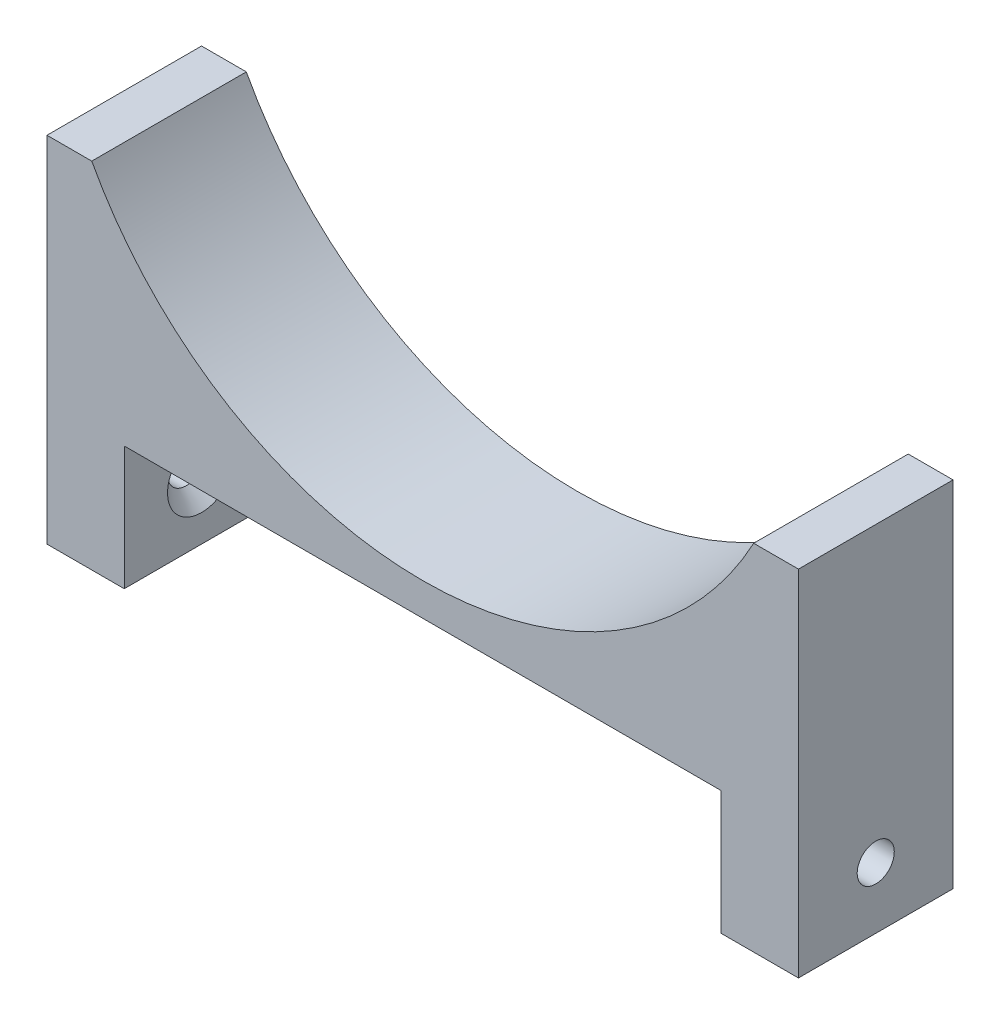
SolidWorks part; units mm, degrees
ref_plane "Płaszczyzna przednia" through (0, 0, 0) normal (0, 0, 1) x (1, 0, 0)
ref_plane "Płaszczyzna górna" through (0, 0, 0) normal (0, 1, 0) x (1, 0, 0)
ref_plane "Płaszczyzna prawa" through (0, 0, 0) normal (1, 0, 0) x (0, 0, -1)
sketch "Sketch1" plane through (0, 0, 0) normal (0, 0, 1) x (1, 0, 0)
  line L0 (-9.7094, -21.2696) -> (-4.7094, -21.2696)
  line L1 (-4.7094, -21.2696) -> (-4.7094, -13.2696)
  line L2 (-4.7094, -13.2696) -> (33.9106, -13.2696)
  line L3 (33.9106, -13.2696) -> (33.9106, -21.2696)
  line L4 (33.9106, -21.2696) -> (38.9106, -21.2696)
  line L5 (38.9106, -21.2696) -> (38.9106, 1.6414)
  line L6 (38.9106, 1.6414) -> (-9.7094, 1.6414)
  line L7 (-9.7094, 1.6414) -> (-9.7094, -21.2696)
  line L8 (14.6006, 13.1504) -> (14.6006, -40.5959) construction
  circle A0 centre (14.6006, 13.1504) radius 24.31
  dimension "D1" = 48.62
  dimension "48.62" = 48.62
  dimension "D2" = 34.42
  dimension "D3" = 5
  dimension "D4" = 5
  dimension "D5" = 24.31
  dimension "D6" = 8
extrude "Boss-Extrude1" add sketch "Sketch1" along normal blind 10 contours L8 A0 L6 L7 L0 L1 L2 | A0 L8 L2 L3 L4 L5 L6
ref_plane "Plane1" through (14.6006, 0, 0) normal (1, 0, 0) x (0, 0, -1)
sketch "Sketch3" plane through (-4.7094, 0, 0) normal (1, 0, 0) x (0, 0, -1)
  line L0 (-10, -21.2696) -> (-10, 1.6414) construction
  line L1 (-10, -13.3333) -> (0, -13.3333)
  line L2 (-10, -13.3333) -> (-10, -21.2696)
  line L3 (-10, -21.2696) -> (0, -21.2696)
  line L4 (0, -13.3333) -> (0, -21.2696)
  line L5 (-10, -13.3333) -> (0, -21.2696) construction
  line L6 (-10, -21.2696) -> (0, -13.3333) construction
  point P4 (-5, -17.3014)
hole_wizard "CSK for M2 Countersunk Flat Head Screw1" positions "Sketch3" profile "Sketch4" countersink size "M2" standard "DIN"
sketch "Sketch4" plane through (-4.7094, -17.3014, 5) normal (0, 1, 0) x (0, 0, -1)
  line L0 (0, 0) -> (0, 17.221)
  line L1 (0, 17.221) -> (1.2, 16.5)
  line L2 (1.2, 16.5) -> (1.2, 1)
  line L3 (1.2, 1) -> (2.2, 0)
  line L5 (2.2, 0) -> (0, 0)
  line L6 (-1.2, 1) -> (-2.2, 0) construction
  line L10 (0, 17.221) -> (-1.2, 16.5) construction
  line L11 (0, -6.35) -> (0, 107.95) construction
  dimension "Hole Dia." = 2.4
  dimension "Hole Depth" = 16.5
  dimension "Near C'Sink Dia." = 4.4
  dimension "Near C'Sink Angle" = 90
  dimension "Drill Angle" = 118
mirror "Mirror2" about plane through (14.6006, 0, 0) normal (1, 0, 0) of "CSK for M2 Countersunk Flat Head Screw1"
